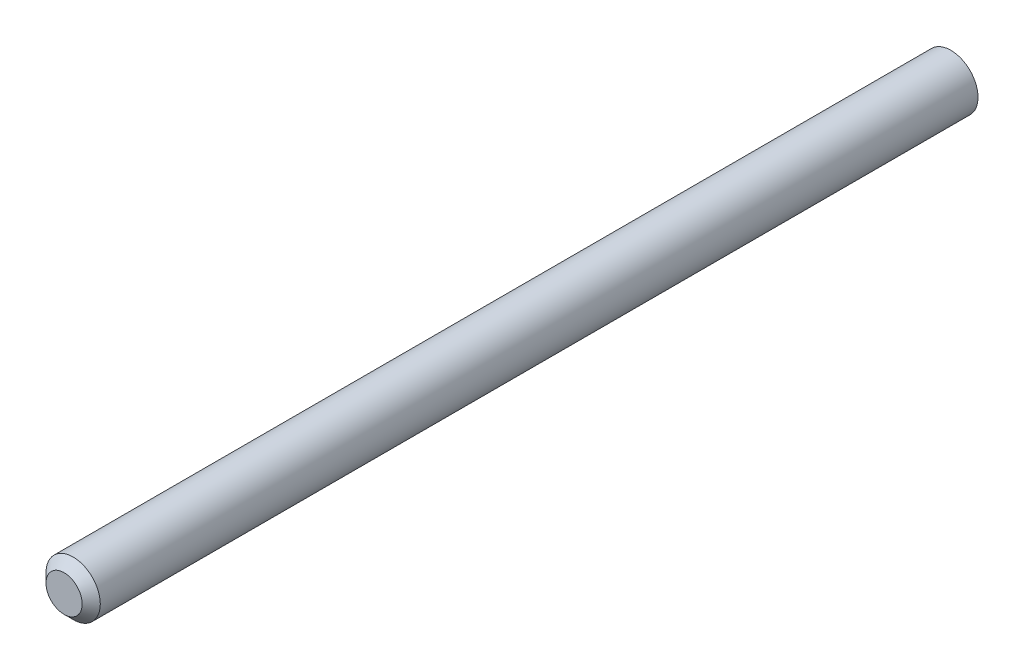
SolidWorks part; units mm, degrees
ref_plane "Front" through (0, 0, 0) normal (0, 0, 1) x (1, 0, 0)
ref_plane "Top" through (0, 0, 0) normal (0, 1, 0) x (1, 0, 0)
ref_plane "Right" through (0, 0, 0) normal (1, 0, 0) x (0, 0, -1)
sketch "Esquisse1" plane through (0, 0, 0) normal (0, 0, 1) x (1, 0, 0)
  circle A0 centre (0, 0) radius 3
  dimension "D1" = 6
extrude "Boss.-Extru.1" add sketch "Esquisse1" along normal blind 98
chamfer "Chanfrein1" distance 1 angle 45 1 edges at (3, 0, 98)
